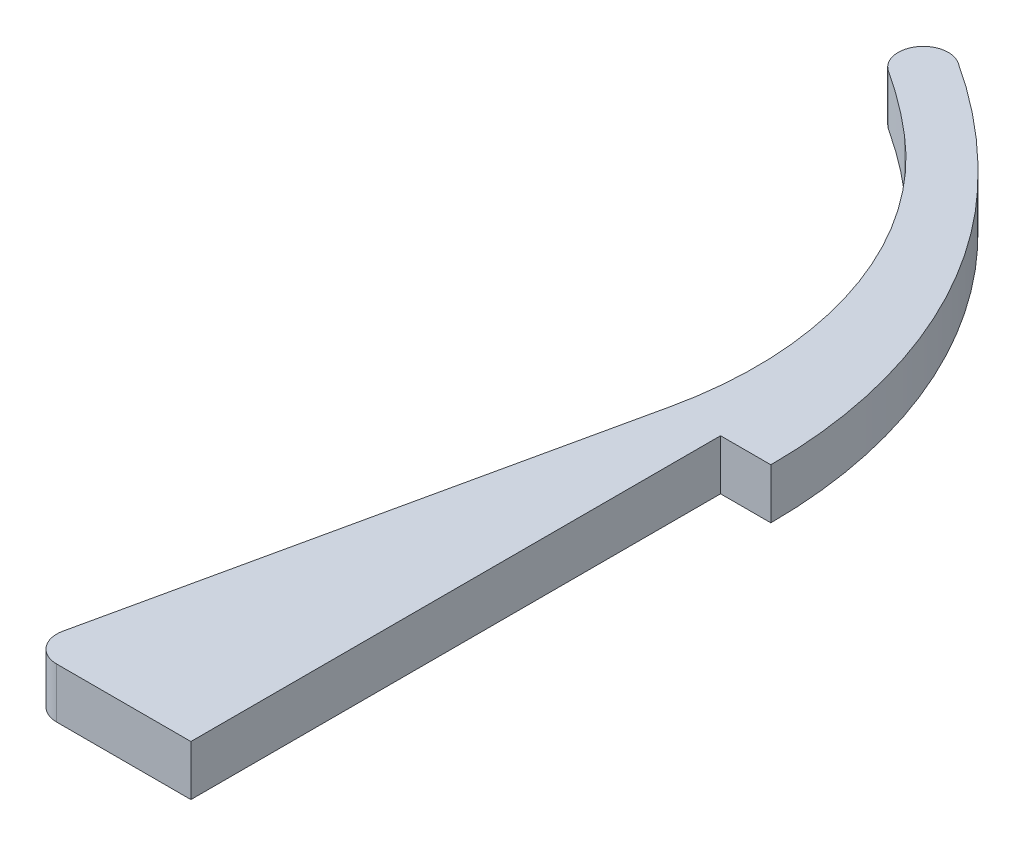
SolidWorks part; units mm, degrees
material "Pine"
ref_plane "Front Plane" through (0, 0, 0) normal (0, 0, 1) x (1, 0, 0)
ref_plane "Top Plane" through (0, 0, 0) normal (0, 1, 0) x (1, 0, 0)
ref_plane "Right Plane" through (0, 0, 0) normal (1, 0, 0) x (0, 0, -1)
sketch "Sketch1" plane through (0, 0, 0) normal (0, 1, 0) x (1, 0, 0)
  line L19 (0, 0) -> (-50.8, 0)
  line L22 (-60.4139, 11.9514) -> (-19.05, 200.5215)
  line L23 (0, 0) -> (0, 200.5215)
  line L25 (0, 200.5215) -> (19.05, 200.5215)
  arc A14 (-50.8, 0) -> (-60.4139, 11.9514) centre (-50.8, 9.8425) cw
  arc A21 (-87.7294, 351.8301) -> (-63.619, 333.7974) centre (-209.55, 163.8174) cw
  arc A23 (-87.7294, 351.8301) -> (-77.3706, 367.8175) centre (-82.55, 359.8238) cw
  arc A25 (-77.3706, 367.8175) -> (-31.9372, 329.7727) centre (-209.55, 163.8174) cw
  arc A29 (-63.619, 333.7974) -> (-19.05, 200.5215) centre (-152.8429, 229.8697) cw
  arc A33 (19.05, 200.5215) -> (-31.9372, 329.7727) centre (-170.2676, 200.5215) ccw
  point P15 (14.2375, 243.2672)
  point P16 (19.05, 227.8042)
  point P17 (-75.4027, 366.9411)
  point P18 (19.05, 217.9385)
  point P19 (19.05, 202.8895)
  dimension "D5" = 9.8425
  dimension "D2" = 19.05
  dimension "D11" = 129.2512
  dimension "D8" = 101.6
  dimension "D9" = 189.3176
  dimension "D4" = 19.05
  dimension "D7" = 19.05
  dimension "D6" = 136.9739
  dimension "D10" = 159.3023
  dimension "D3" = 50.8
  dimension "D13" = 200.5215
extrude "Boss-Extrude1" add sketch "Sketch1" along normal blind 19.05
